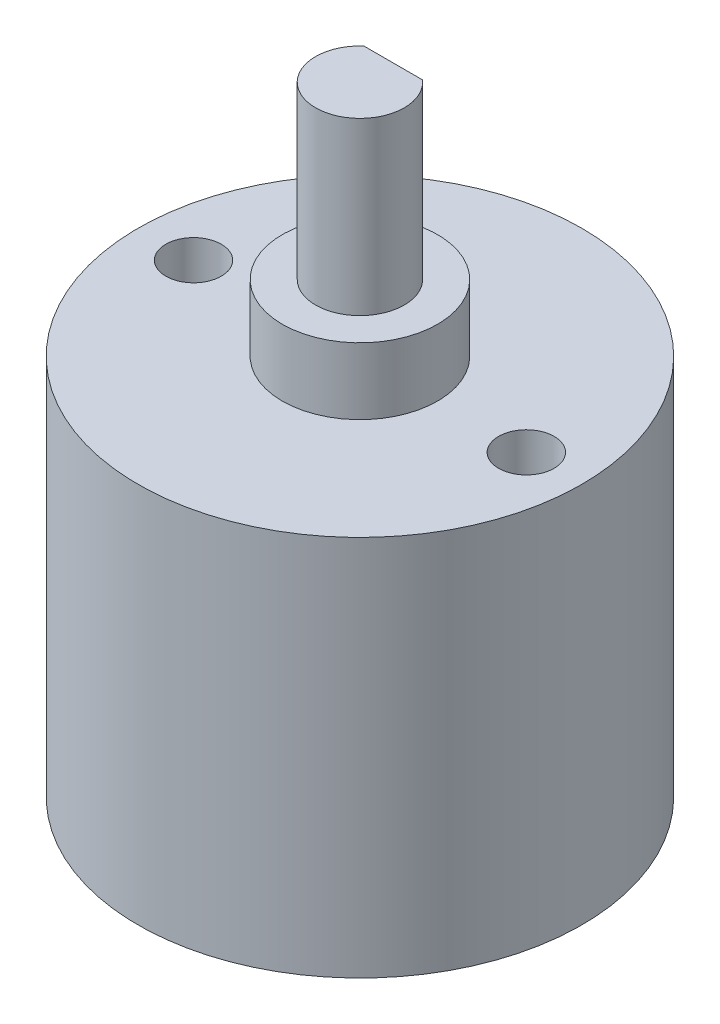
SolidWorks part; units mm, degrees
ref_plane "Front Plane" through (0, 0, 0) normal (0, 0, 1) x (1, 0, 0)
ref_plane "Top Plane" through (0, 0, 0) normal (0, 1, 0) x (1, 0, 0)
ref_plane "Right Plane" through (0, 0, 0) normal (1, 0, 0) x (0, 0, -1)
sketch "Sketch1" plane through (0, 0, 0) normal (0, 1, 0) x (1, 0, 0)
  circle A0 centre (0, 0) radius 10
  dimension "D1" = 20
extrude "Boss-Extrude1" add sketch "Sketch1" along normal blind 17.2
sketch "Sketch2" plane through (0, 17.2, 0) normal (0, 1, 0) x (1, 0, 0)
  circle A0 centre (0, 0) radius 3.5
  dimension "D1" = 7
extrude "Boss-Extrude2" add sketch "Sketch2" along normal blind 3
sketch "Sketch3" plane through (0, 20.2, 0) normal (0, 1, 0) x (1, 0, 0)
  line L0 (-1.3229, 1.5) -> (1.3229, 1.5)
  line L1 (0, 0) -> (2.8596, 0) construction
  circle A0 centre (0, 0) radius 2
  dimension "D1" = 4
  dimension "D2" = 1.5
extrude "Boss-Extrude3" add sketch "Sketch3" along normal blind 7.7
sketch "Sketch4" plane through (0, 17.2, 0) normal (0, 1, 0) x (1, 0, 0)
  line L0 (0, 0) -> (0, 5.4532) construction
  line L1 (7.5, 0) -> (-7.5, 0) construction
  circle A0 centre (-7.5, 0) radius 1.25
  circle A1 centre (7.5, 0) radius 1.25
  dimension "D2" = 2.5
  dimension "D3" = 2.5
  dimension "D1" = 15
  dimension "D4" = 7.5
extrude "Cut-Extrude1" cut sketch "Sketch4" against normal blind 3.175
